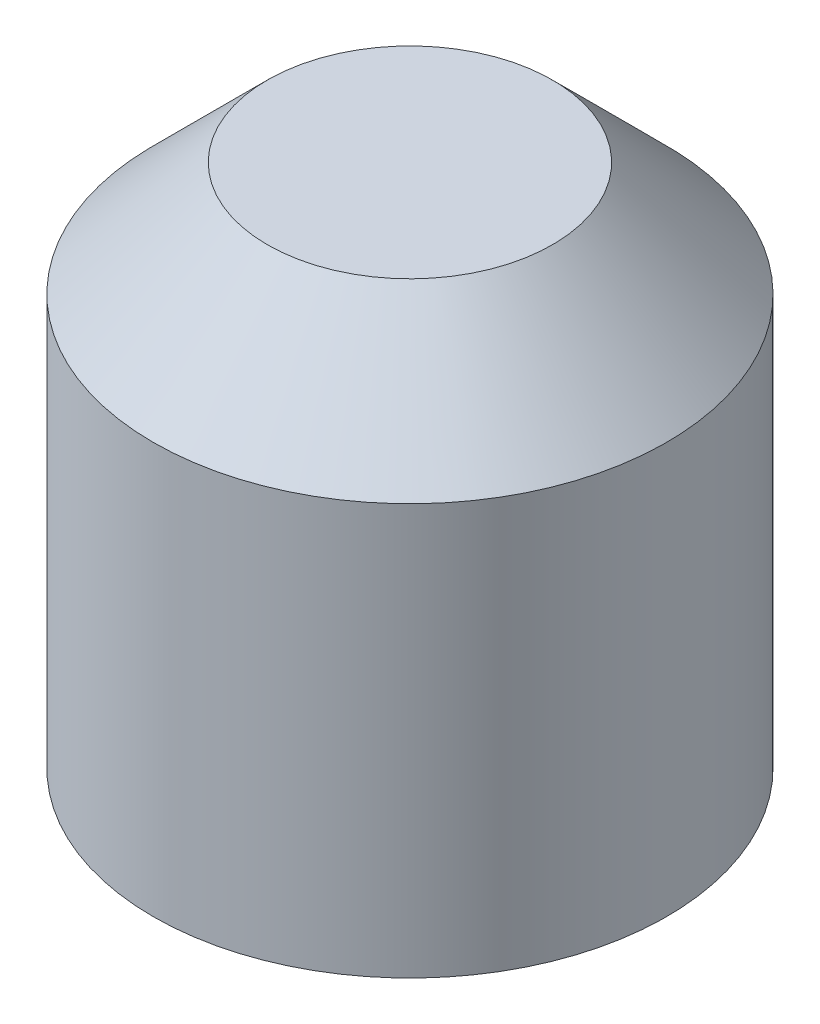
SolidWorks part; units mm, degrees
ref_plane "Front Plane" through (0, 0, 0) normal (0, 0, 1) x (1, 0, 0)
ref_plane "Top Plane" through (0, 0, 0) normal (0, 1, 0) x (1, 0, 0)
ref_plane "Right Plane" through (0, 0, 0) normal (1, 0, 0) x (0, 0, -1)
sketch "Sketch1" plane through (0, 0, 0) normal (0, 1, 0) x (1, 0, 0)
  circle A0 centre (0, 0) radius 45
  dimension "D1" = 90
extrude "Boss-Extrude1" add sketch "Sketch1" along normal blind 92
chamfer "Chamfer1" distance 20 angle 45 1 edges at (0, 92, 45)
